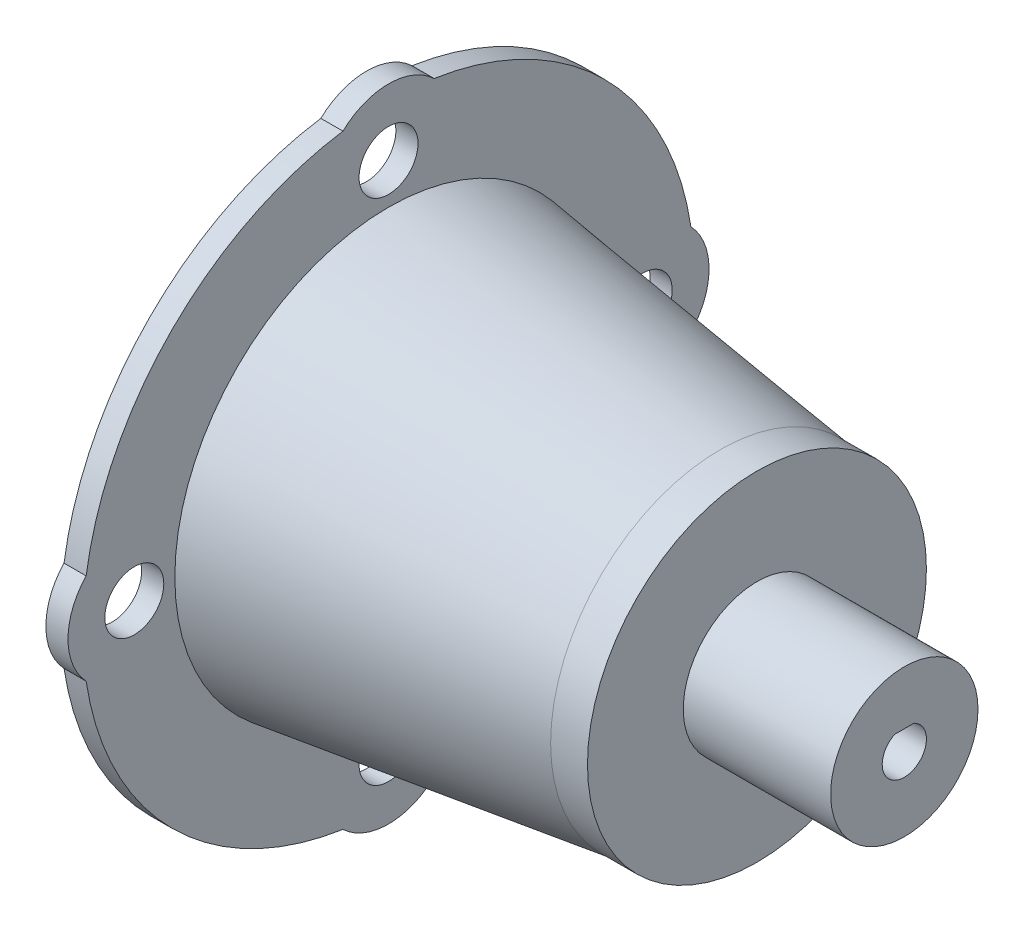
SolidWorks part; units mm, degrees
ref_plane "Alzado" through (0, 0, 0) normal (0, 0, 1) x (1, 0, 0)
ref_plane "Planta" through (0, 0, 0) normal (0, 1, 0) x (1, 0, 0)
ref_plane "Vista lateral" through (0, 0, 0) normal (1, 0, 0) x (0, 0, -1)
sketch "Croquis1" plane through (0, 0, 0) normal (1, 0, 0) x (0, 0, -1)
  line L0 (0, 56.9873) -> (0, -60.5006) construction
  line L1 (-34.5, 0) -> (0, 34.5) construction
  line L2 (0, 34.5) -> (34.5, 0) construction
  line L3 (34.5, 0) -> (0, -34.5) construction
  line L4 (0, -34.5) -> (-34.5, 0) construction
  circle A0 centre (0, 0) radius 34.5 construction
  circle A1 centre (0, 34.5) radius 4
  circle A2 centre (34.5, 0) radius 4
  circle A3 centre (0, -34.5) radius 4
  circle A4 centre (-34.5, 0) radius 4
  circle A5 centre (-34.5, 0) radius 9
  circle A6 centre (0, 34.5) radius 9
  circle A7 centre (34.5, 0) radius 9
  circle A8 centre (0, -34.5) radius 9
  circle A9 centre (0, 0) radius 41.5
  circle A10 centre (0, 0) radius 27.5
  circle A11 centre (0, 0) radius 20
  point P16 (0, 0)
  dimension "D1" = 69
  dimension "D2" = 8
  dimension "D4" = 34.5
  dimension "D9" = 40
  dimension "D5" = 34.5
  dimension "D6" = 5
  dimension "D7" = 7
  dimension "D8" = 7
  dimension "D3" = 4
extrude "Saliente-Extruir1" add sketch "Croquis1" along normal blind 3 contours A9 A8 | A10 A8 A9 A3 | A8 A10 | A7 A10 | A10 A7 A9 A2 | A9 A7 | A9 A6 | A10 A6 A9 A1 | A6 A10 | A5 A10 | A10 A5 A9 A4 | A9 A5 | A7 A10 A6 A5 A8 A11 | A10 A7 A9 A6 | A10 A5 A9 A8 | A10 A8 A9 A7 | A10 A6 A9 A5
sketch "Croquis2" plane through (3, 0, 0) normal (1, 0, 0) x (0, 0, -1)
  circle A0 centre (0, 0) radius 20 construction
  circle A1 centre (0, 0) radius 20
extrude "Extruir-Lámina2" add sketch "Croquis2" along normal blind 30 thin
sketch "Croquis3" plane through (33, 0, 0) normal (1, 0, 0) x (0, 0, -1)
  circle A1 centre (0, 0) radius 23
  circle A2 centre (0, 0) radius 23
  dimension "D1" = 0
extrude "Saliente-Extruir2" add sketch "Croquis3" along normal blind 20
sketch "Croquis4" plane through (33, 0, 0) normal (-1, 0, 0) x (0, 0, 1)
  circle A0 centre (0, 0) radius 4.4
  dimension "D1" = 8.8
extrude "Saliente-Extruir3" add sketch "Croquis4" along normal blind 20
sketch "Croquis5" plane through (0, 0, 0) normal (0, 1, 0) x (1, 0, 0)
  line L0 (48, -23) -> (3, -29)
  line L1 (3, -23) -> (53, -23) construction
  line L2 (3, -41.0362) -> (3, -6.1869) construction
  line L3 (3, -23) -> (53, -23) construction
  line L4 (3, -29) -> (3, -23)
  line L5 (3, -23) -> (48, -23)
  line L6 (-12.2622, 0) -> (66.5074, 0) construction
  dimension "D1" = 6
  dimension "D2" = 45
revolve "Revolución1" add sketch "Croquis5" angle 360 about L6
sketch "Croquis6" plane through (53, 0, 0) normal (1, 0, 0) x (0, 0, -1)
  line L0 (-1.3077, 2.7) -> (1.3077, 2.7)
  circle A0 centre (0, 0) radius 10
  arc A1 (-1.3077, 2.7) -> (1.3077, 2.7) centre (0, 0) ccw
  dimension "D1" = 6
  dimension "D2" = 20
  dimension "D3" = 2.7
extrude "Saliente-Extruir4" add sketch "Croquis6" along normal blind 20
